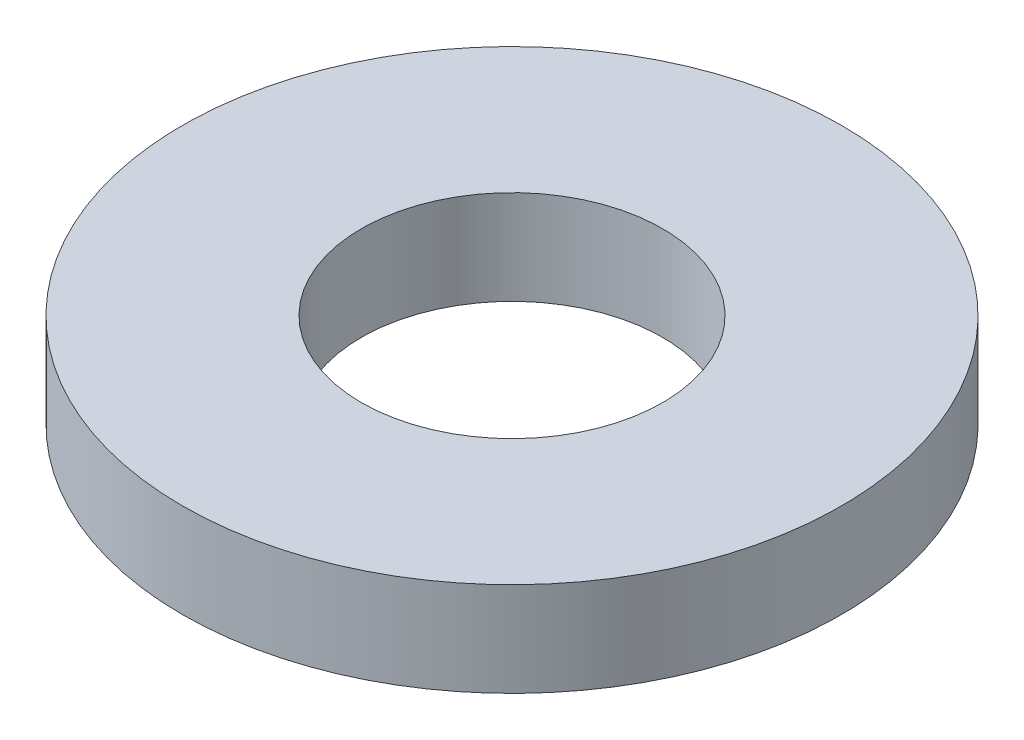
SolidWorks part; units mm, degrees
ref_plane "Front Plane" through (0, 0, 0) normal (0, 0, 1) x (1, 0, 0)
ref_plane "Top Plane" through (0, 0, 0) normal (0, 1, 0) x (1, 0, 0)
ref_plane "Right Plane" through (0, 0, 0) normal (1, 0, 0) x (0, 0, -1)
sketch "Sketch1" plane through (0, 0, 0) normal (0, 1, 0) x (1, 0, 0)
  circle A0 centre (0, 0) radius 8
  circle A1 centre (0, 0) radius 17.5
  dimension "D1" = 35
  dimension "D2" = 16
extrude "Boss-Extrude1" add sketch "Sketch1" along normal blind 5
